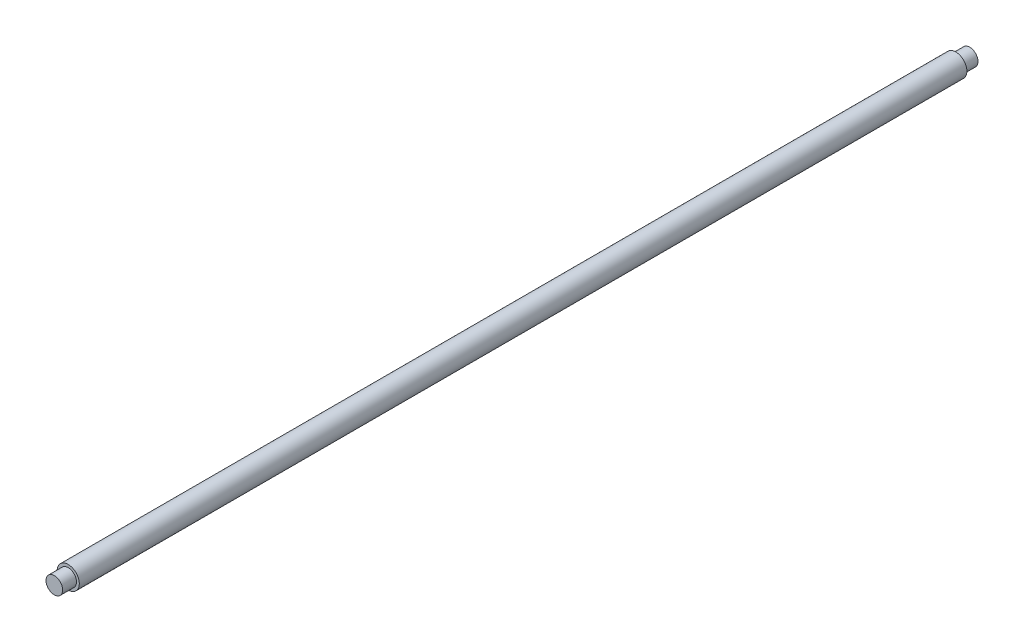
SolidWorks part; units mm, degrees
ref_plane "정면" through (0, 0, 0) normal (0, 0, 1) x (1, 0, 0)
ref_plane "윗면" through (0, 0, 0) normal (0, 1, 0) x (1, 0, 0)
ref_plane "우측면" through (0, 0, 0) normal (1, 0, 0) x (0, 0, -1)
sketch "스케치1" plane through (0, 0, 0) normal (0, 0, 1) x (1, 0, 0)
  circle A0 centre (0, 0) radius 3
  dimension "D1" = 6
extrude "보스-돌출1" add sketch "스케치1" along normal blind 330
ref_plane "평면1" through (0, 0, 5) normal (0, 0, -1) x (-1, 0, 0)
sketch "스케치2" plane through (0, 0, 5) normal (0, 0, -1) x (-1, 0, 0)
  circle A0 centre (0, 0) radius 4
  dimension "D1" = 8
extrude "보스-돌출2" add sketch "스케치2" against normal blind 320 contours A0
